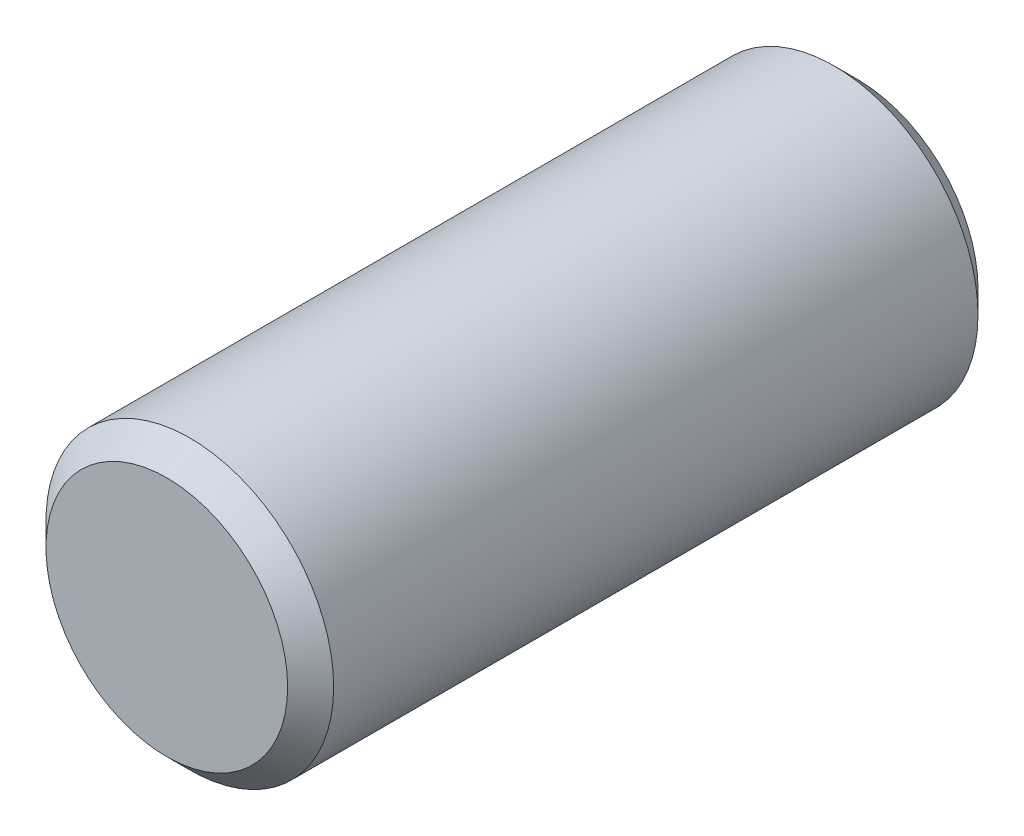
SolidWorks part; units mm, degrees
material "2A12"
ref_plane "前视基准面" through (0, 0, 0) normal (0, 0, 1) x (1, 0, 0)
ref_plane "上视基准面" through (0, 0, 0) normal (0, 1, 0) x (1, 0, 0)
ref_plane "右视基准面" through (0, 0, 0) normal (1, 0, 0) x (0, 0, -1)
sketch "草图1" plane through (0, 0, 0) normal (0, 0, 1) x (1, 0, 0)
  circle A0 centre (0, 0) radius 1.25
  dimension "D1" = 2.5
extrude "凸台-拉伸1" add sketch "草图1" along normal blind 6
chamfer "倒角1" distance 0.2 angle 45 2 edges at (1.25, 0, 6) (1.25, 0, 0)
